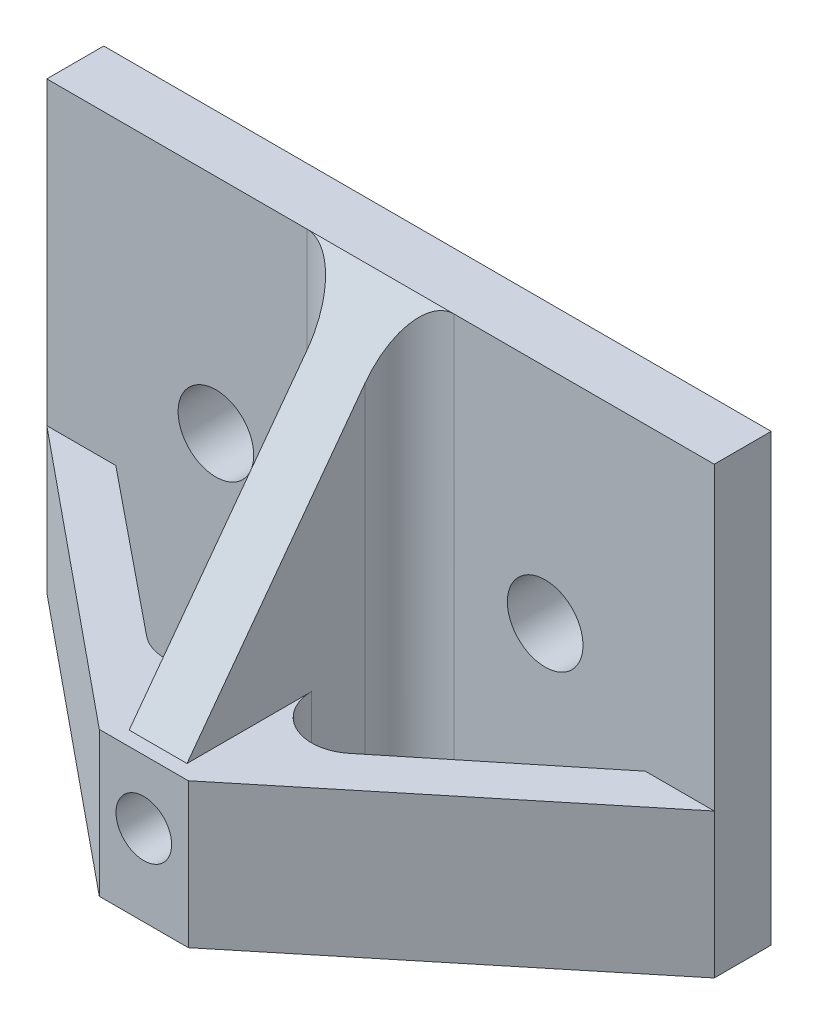
SolidWorks part; units mm, degrees
ref_plane "Front Plane" through (0, 0, 0) normal (0, 0, 1) x (1, 0, 0)
ref_plane "Top Plane" through (0, 0, 0) normal (0, 1, 0) x (1, 0, 0)
ref_plane "Right Plane" through (0, 0, 0) normal (1, 0, 0) x (0, 0, -1)
sketch "Sketch1" plane through (0, 0, 0) normal (0, 1, 0) x (1, 0, 0)
  line L1 (19.05, 8.382) -> (-19.05, 8.382)
  line L2 (19.05, 8.382) -> (19.05, -8.382)
  line L3 (19.05, -8.382) -> (-19.05, -8.382)
  line L4 (-19.05, 8.382) -> (-19.05, -8.382)
  line L5 (19.05, 8.382) -> (-19.05, -8.382) construction
  line L6 (19.05, -8.382) -> (-19.05, 8.382) construction
  point P0 (0, 0)
  dimension "D1" = 16.764
  dimension "D2" = 38.1
extrude "Boss-Extrude1" add sketch "Sketch1" along normal blind 25.4
sketch "Sketch3" plane through (0, 0, 0) normal (0, -1, 0) x (1, 0, 0)
  line L0 (-2.54, 8.382) -> (-19.05, -5.1326)
  line L1 (-19.05, 8.382) -> (19.05, 8.382) construction
  line L2 (-19.05, -8.382) -> (-19.05, 8.382) construction
  line L3 (-19.05, -5.1326) -> (-19.05, 8.382)
  line L4 (-19.05, 8.382) -> (-2.54, 8.382)
  line L5 (0, 12.0238) -> (0, -9.2976) construction
  line L6 (19.05, -5.1326) -> (19.05, 8.382)
  line L7 (19.05, 8.382) -> (2.54, 8.382)
  line L8 (2.54, 8.382) -> (19.05, -5.1326)
  dimension "D1" = 2.54
  dimension "D2" = 21.336
extrude "Cut-Extrude1" cut sketch "Sketch3" against normal through all
sketch "Sketch5" plane through (0, 0, 0) normal (0, -1, 0) x (1, 0, 0)
  line L0 (-4.191, -5.1326) -> (-15.113, -5.1326)
  line L1 (-15.113, -5.1326) -> (-5.791, 2.4281)
  line L2 (-1.651, 0.4554) -> (-1.651, -2.5926)
  line L3 (0, 0) -> (0, -13.6107) construction
  line L4 (1.651, 0.4554) -> (1.651, -2.5926)
  line L5 (15.113, -5.1326) -> (5.791, 2.4281)
  line L6 (4.191, -5.1326) -> (15.113, -5.1326)
  arc A0 (-1.651, 0.4554) -> (-5.791, 2.4281) centre (-4.191, 0.4554) ccw
  arc A1 (-1.651, -2.5926) -> (-4.191, -5.1326) centre (-4.191, -2.5926) cw
  arc A2 (1.651, 0.4554) -> (5.791, 2.4281) centre (4.191, 0.4554) cw
  arc A3 (1.651, -2.5926) -> (4.191, -5.1326) centre (4.191, -2.5926) ccw
  dimension "D1" = 2.54
  dimension "D2" = 2.54
  dimension "D3" = 3.048
  dimension "D4" = 10.922
  dimension "D5" = 1.651
extrude "Cut-Extrude3" cut sketch "Sketch5" against normal through all
sketch "Sketch6" plane through (0, 25.4, 0) normal (0, 1, 0) x (1, 0, 0)
  line L0 (1.651, -0.4554) -> (1.651, -11.683)
  line L1 (1.651, -11.683) -> (19.05, 5.1326)
  line L2 (19.05, 5.1326) -> (4.191, 5.1326)
  line L3 (4.191, 5.1326) -> (1.651, -0.4554)
  line L4 (0, 10.9405) -> (0, -10.0147) construction
  line L5 (-4.191, 5.1326) -> (-1.651, -0.4554)
  line L6 (-19.05, 5.1326) -> (-4.191, 5.1326)
  line L7 (-1.651, -11.683) -> (-19.05, 5.1326)
  line L8 (-1.651, -0.4554) -> (-1.651, -11.683)
extrude "Cut-Extrude4" cut sketch "Sketch6" against normal blind 17.145
sketch "Sketch7" plane through (0, 0, -8.382) normal (0, 0, -1) x (-1, 0, 0)
  line L0 (-19.05, 25.4) -> (-19.05, 0) construction
  line L1 (-19.05, 0) -> (19.05, 0) construction
  line L2 (0, 27.5255) -> (0, -4) construction
  circle A0 centre (-9.398, 12.7) radius 2.159
  circle A1 centre (9.398, 12.7) radius 2.159
  dimension "D1" = 4.318
  dimension "D2" = 9.652
  dimension "D3" = 12.7
extrude "Cut-Extrude5" cut sketch "Sketch7" against normal through all
sketch "Sketch9" plane through (1.651, 0, 0) normal (1, 0, 0) x (0, 0, -1)
  line L0 (5.1326, 25.4) -> (-7.5668, 8.255)
  line L1 (-0.4554, 8.255) -> (-8.382, 8.255) construction
  line L3 (-8.382, 25.4) -> (2.5926, 25.4) construction
  line L4 (-7.5668, 25.4) -> (5.1326, 25.4)
  line L5 (-7.5668, 8.255) -> (-10.0753, 8.255)
  line L6 (-10.0753, 8.255) -> (-10.0753, 25.4)
  line L7 (-10.0753, 25.4) -> (-7.5668, 25.4)
  dimension "D1" = 21.336
extrude "Cut-Extrude6" cut sketch "Sketch9" against normal through all both and the other way through all
sketch "Sketch10" plane through (0, 0, 8.382) normal (0, 0, 1) x (1, 0, 0)
  circle A0 centre (0, 4.6231) radius 1.5875
  dimension "D1" = 3.175
extrude "Cut-Extrude7" cut sketch "Sketch10" against normal blind 9.398
